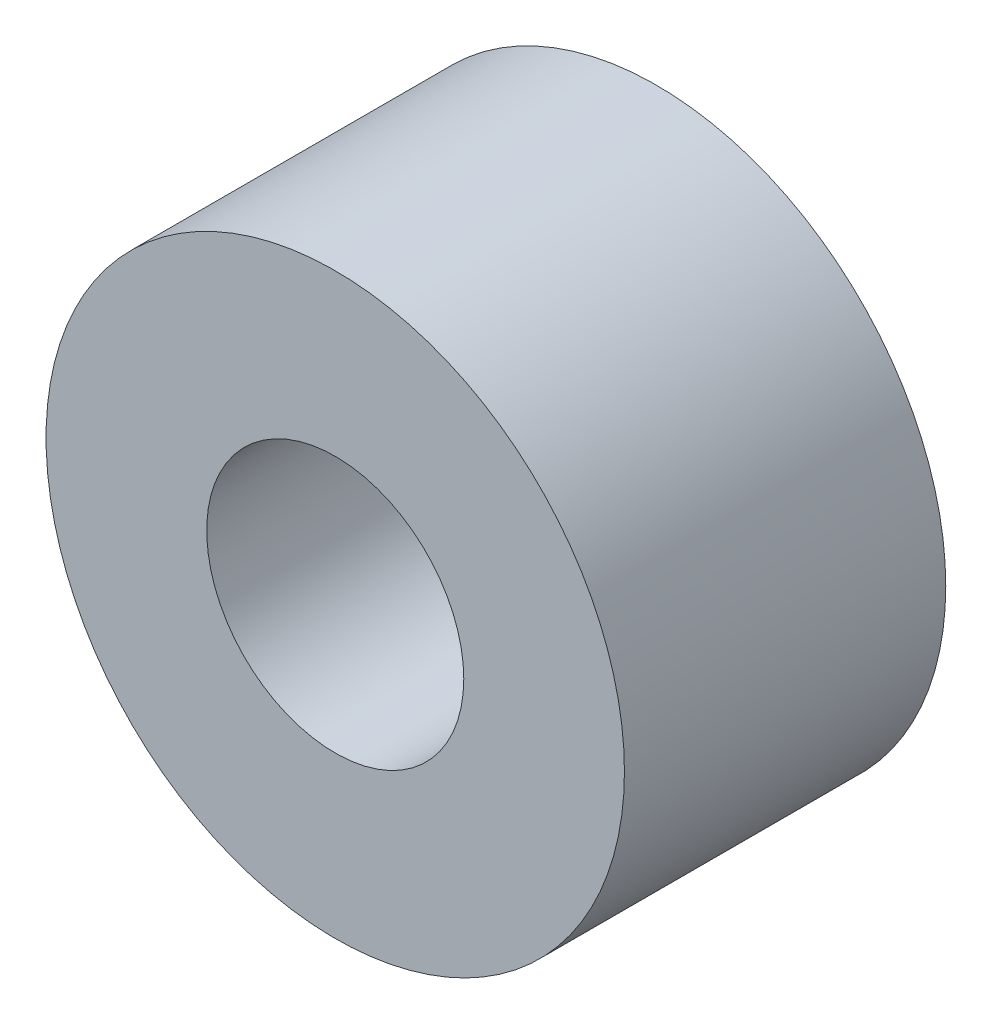
SolidWorks part; units mm, degrees
ref_plane "Piano frontale" through (0, 0, 0) normal (0, 0, 1) x (1, 0, 0)
ref_plane "Piano superiore" through (0, 0, 0) normal (0, 1, 0) x (1, 0, 0)
ref_plane "Piano destro" through (0, 0, 0) normal (1, 0, 0) x (0, 0, -1)
sketch "Schizzo1" plane through (0, 0, 0) normal (0, 0, 1) x (1, 0, 0)
  circle A0 centre (0, 0) radius 4
  circle A1 centre (0, 0) radius 9
  dimension "D1" = 8
  dimension "D2" = 5
extrude "Estrusione-Estrusione1" add sketch "Schizzo1" along normal blind 10
